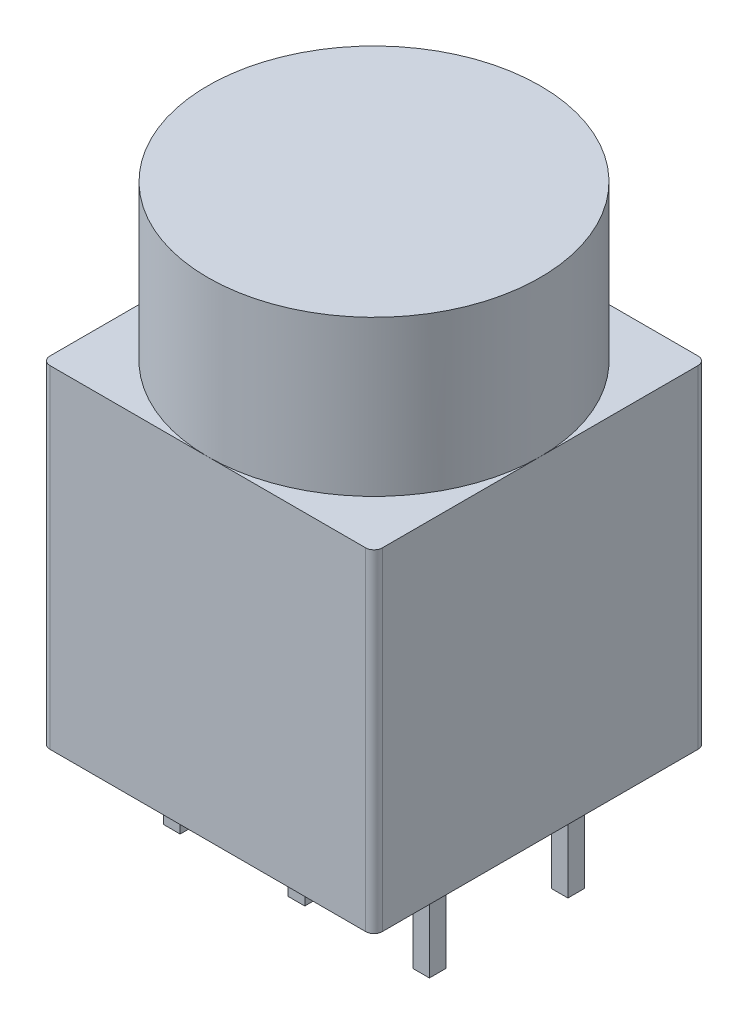
SolidWorks part; units mm, degrees
ref_plane "Front Plane" through (0, 0, 0) normal (0, 0, 1) x (1, 0, 0)
ref_plane "Top Plane" through (0, 0, 0) normal (0, 1, 0) x (1, 0, 0)
ref_plane "Right Plane" through (0, 0, 0) normal (1, 0, 0) x (0, 0, -1)
ref_plane "PY_p28_40" through (0, 28.4, 0) normal (0, 1, 0) x (1, 0, 0)
sketch "Body_Sk1" plane through (0, 28.4, 0) normal (0, 1, 0) x (1, 0, 0)
  line L0 (30.3, 28.5) -> (41.7, 28.5)
  line L1 (42, 28.2) -> (42, 16.8)
  line L2 (41.7, 16.5) -> (30.3, 16.5)
  line L3 (30, 16.8) -> (30, 28.2)
  arc A0 (30, 28.2) -> (30.3, 28.5) centre (30.3, 28.2) cw
  arc A1 (41.7, 28.5) -> (42, 28.2) centre (41.7, 28.2) cw
  arc A2 (42, 16.8) -> (41.7, 16.5) centre (41.7, 16.8) cw
  arc A3 (30.3, 16.5) -> (30, 16.8) centre (30.3, 16.8) cw
extrude "Body" add sketch "Body_Sk1" against normal blind 12
sketch "Pins_Sk2" plane through (0, 28.4, 0) normal (0, 1, 0) x (1, 0, 0)
  line L0 (31.2, 25.3) -> (31.8, 25.3)
  line L1 (31.8, 25.3) -> (31.8, 24.7)
  line L2 (31.8, 24.7) -> (31.2, 24.7)
  line L3 (31.2, 24.7) -> (31.2, 25.3)
  line L4 (31.2, 20.3) -> (31.8, 20.3)
  line L5 (31.8, 20.3) -> (31.8, 19.7)
  line L6 (31.8, 19.7) -> (31.2, 19.7)
  line L7 (31.2, 19.7) -> (31.2, 20.3)
  line L8 (35.7, 25.3) -> (36.3, 25.3)
  line L9 (36.3, 25.3) -> (36.3, 24.7)
  line L10 (36.3, 24.7) -> (35.7, 24.7)
  line L11 (35.7, 24.7) -> (35.7, 25.3)
  line L12 (35.7, 20.3) -> (36.3, 20.3)
  line L13 (36.3, 20.3) -> (36.3, 19.7)
  line L14 (36.3, 19.7) -> (35.7, 19.7)
  line L15 (35.7, 19.7) -> (35.7, 20.3)
  line L16 (40.2, 25.3) -> (40.8, 25.3)
  line L17 (40.8, 25.3) -> (40.8, 24.7)
  line L18 (40.8, 24.7) -> (40.2, 24.7)
  line L19 (40.2, 24.7) -> (40.2, 25.3)
  line L20 (40.2, 20.3) -> (40.8, 20.3)
  line L21 (40.8, 20.3) -> (40.8, 19.7)
  line L22 (40.8, 19.7) -> (40.2, 19.7)
  line L23 (40.2, 19.7) -> (40.2, 20.3)
extrude "Pins" add sketch "Pins_Sk2" against normal blind 15.5
sketch "Cap_Sk3" plane through (0, 28.4, 0) normal (0, 1, 0) x (1, 0, 0)
  circle A0 centre (36, 22.5) radius 6
extrude "Cap" add sketch "Cap_Sk3" along normal blind 5.6
